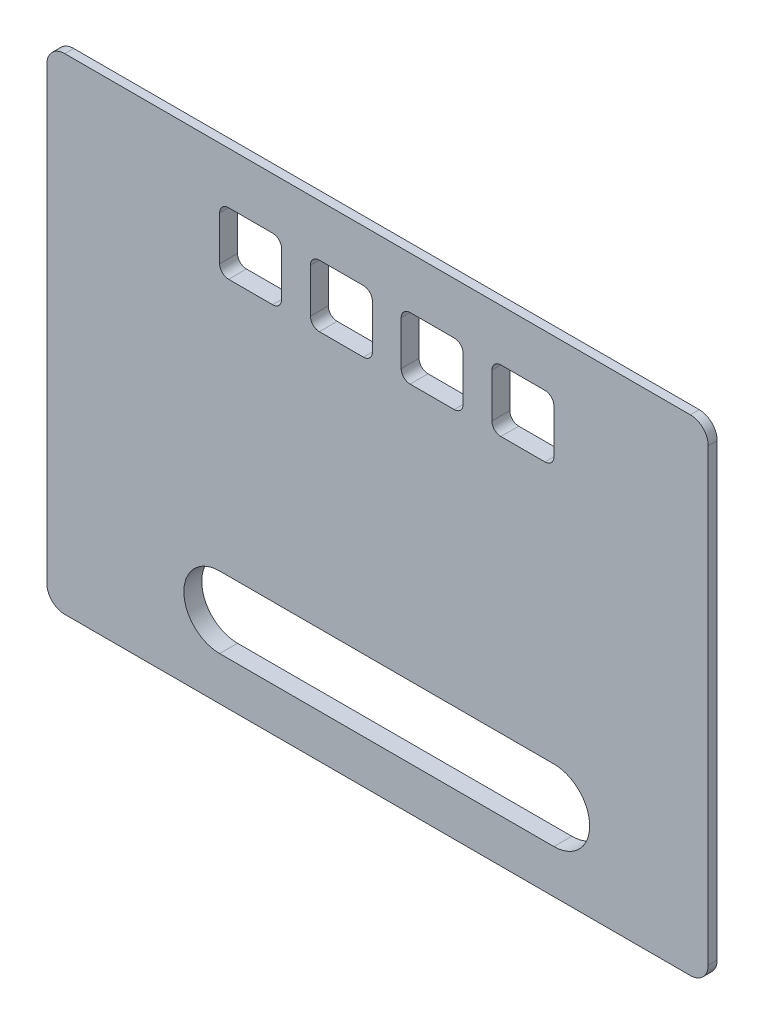
SolidWorks part; units mm, degrees
ref_plane "Спереди" through (0, 0, 0) normal (0, 0, 1) x (1, 0, 0)
ref_plane "Сверху" through (0, 0, 0) normal (0, 1, 0) x (1, 0, 0)
ref_plane "Справа" through (0, 0, 0) normal (1, 0, 0) x (0, 0, -1)
other "Configuration Table"
sketch "Эскиз1" plane through (0, 0, 0) normal (0, 0, 1) x (1, 0, 0)
  line L1 (1, 3) -> (106, 3)
  line L2 (1, 3) -> (1, 77)
  line L3 (1, 77) -> (106, 77)
  line L4 (106, 3) -> (106, 77)
extrude "Бобышка-Вытянуть1" add sketch "Эскиз1" along normal blind 3
sketch "Эскиз2" plane through (0, 0, 0) normal (0, 0, 1) x (1, 0, 0)
  line L1 (-2, 0) -> (109, 0)
  line L2 (-2, 0) -> (-2, 80)
  line L3 (-2, 80) -> (109, 80)
  line L4 (109, 0) -> (109, 80)
extrude "Бобышка-Вытянуть2" add sketch "Эскиз2" along normal blind 1.5 from offset 1.5
sketch "Эскиз3" plane through (0.75, 0, 3) normal (0, 0, 1) x (1, 0, 0)
  line L0 (26.25, 13.3) -> (82.35, 13.3) construction
  line L1 (26.25, 62.45) -> (36.65, 62.45)
  line L2 (26.25, 62.45) -> (26.25, 72.85)
  line L3 (26.25, 72.85) -> (36.65, 72.85)
  line L4 (36.65, 62.45) -> (36.65, 72.85)
  line L5 (41.483, 62.45) -> (51.883, 62.45)
  line L6 (41.483, 62.45) -> (41.483, 72.85)
  line L7 (41.483, 72.85) -> (51.883, 72.85)
  line L8 (51.883, 62.45) -> (51.883, 72.85)
  line L9 (56.717, 62.45) -> (67.117, 62.45)
  line L10 (56.717, 62.45) -> (56.717, 72.85)
  line L11 (56.717, 72.85) -> (67.117, 72.85)
  line L12 (67.117, 62.45) -> (67.117, 72.85)
  line L13 (71.95, 62.45) -> (82.35, 62.45)
  line L14 (71.95, 62.45) -> (71.95, 72.85)
  line L15 (71.95, 72.85) -> (82.35, 72.85)
  line L16 (82.35, 62.45) -> (82.35, 72.85)
  line L19 (26.25, 19.3) -> (82.35, 19.3)
  line L20 (26.25, 7.3) -> (82.35, 7.3)
  arc A2 (26.25, 19.3) -> (26.25, 7.3) centre (26.25, 13.3) ccw
  arc A3 (82.35, 7.3) -> (82.35, 19.3) centre (82.35, 13.3) ccw
  point P18 (54.3, 13.3)
extrude "Вырез-Вытянуть1" cut sketch "Эскиз3" against normal blind 5
sketch "Эскиз4" plane through (0, 0, 0) normal (0, 0, 1) x (1, 0, 0)
  line L1 (1, 77) -> (106, 77)
  line L2 (1, 77) -> (1, 78.5)
  line L3 (1, 78.5) -> (106, 78.5)
  line L4 (106, 77) -> (106, 78.5)
extrude "top_rear_inner_extension_1p5mm" add sketch "Эскиз4" along normal blind 3
sketch "Эскиз5" plane through (0, 0, 0) normal (0, 0, 1) x (1, 0, 0)
  line L1 (-2, 80) -> (109, 80)
  line L2 (-2, 80) -> (-2, 81.5)
  line L3 (-2, 81.5) -> (109, 81.5)
  line L4 (109, 80) -> (109, 81.5)
extrude "top_rear_outer_skin_extension_1p5mm" add sketch "Эскиз5" along normal blind 1.5 from offset 1.5
fillet "tool_D3_R1p5_button_corners" radius 1.5 16 edges at (72.7, 72.85, 1.5) (83.1, 72.85, 1.5) (83.1, 62.45, 1.5) (72.7, 62.45, 1.5) (57.467, 72.85, 1.5) (67.867, 72.85, 1.5) (67.867, 62.45, 1.5) (57.467, 62.45, 1.5) (42.233, 72.85, 1.5) (52.633, 72.85, 1.5) (52.633, 62.45, 1.5) (42.233, 62.45, 1.5) (27, 62.45, 1.5) (37.4, 62.45, 1.5) (37.4, 72.85, 1.5) (27, 72.85, 1.5)
fillet "tool_D3_R3_top_outer_contour" radius 3 4 edges at (-2, 81.5, 2.25) (109, 81.5, 2.25) (109, 0, 2.25) (-2, 0, 2.25)
sketch "Эскиз6" plane through (0, 0, 0) normal (0, 0, -1) x (-1, 0, 0)
  circle A0 centre (-1, 10) radius 1.5
  circle A1 centre (-106, 10) radius 1.5
  circle A2 centre (-1, 40.75) radius 1.5
  circle A3 centre (-106, 40.75) radius 1.5
  circle A4 centre (-1, 71.5) radius 1.5
  circle A5 centre (-106, 71.5) radius 1.5
extrude "top_planar_edge_semicircle_pockets_D3_depth1p5_6x" cut sketch "Эскиз6" against normal blind 1.5
